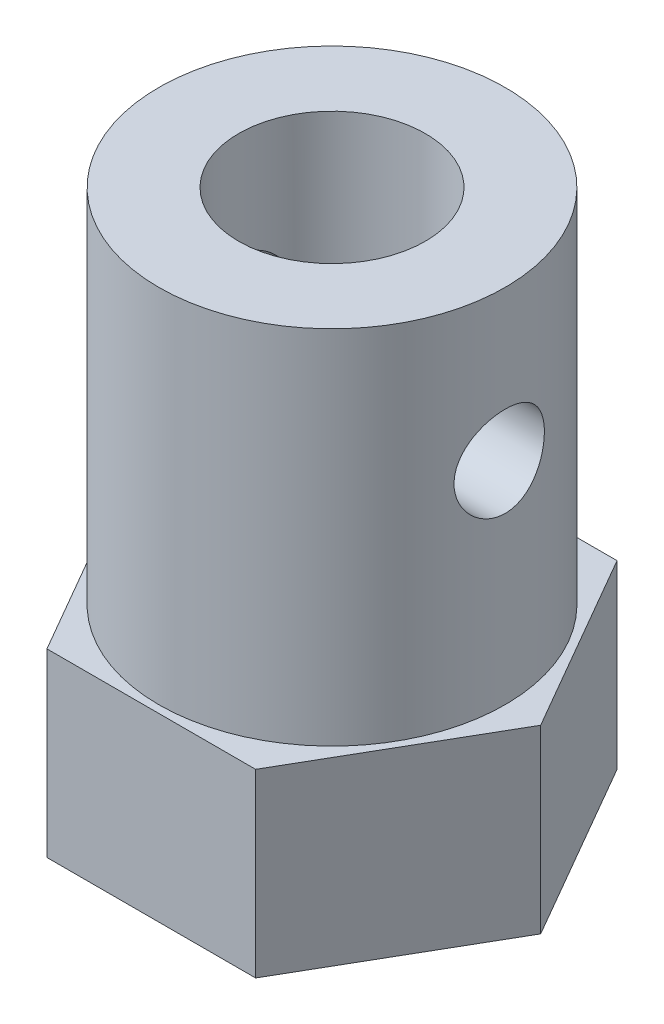
SolidWorks part; units mm, degrees
ref_plane "Front Plane" through (0, 0, 0) normal (0, 0, 1) x (1, 0, 0)
ref_plane "Top Plane" through (0, 0, 0) normal (0, 1, 0) x (1, 0, 0)
ref_plane "Right Plane" through (0, 0, 0) normal (1, 0, 0) x (0, 0, -1)
sketch "Sketch1" plane through (0, 0, 0) normal (0, 1, 0) x (1, 0, 0)
  line L1 (6.9282, 0) -> (3.4641, 6)
  line L2 (3.4641, 6) -> (-3.4641, 6)
  line L3 (-3.4641, 6) -> (-6.9282, 0)
  line L4 (-6.9282, 0) -> (-3.4641, -6)
  line L5 (-3.4641, -6) -> (3.4641, -6)
  line L6 (3.4641, -6) -> (6.9282, 0)
  circle A0 centre (0, 0) radius 6 construction
  circle A1 centre (0, 0) radius 1.5
  dimension "D2" = 3
  dimension "D1" = 12
extrude "Boss-Extrude1" add sketch "Sketch1" along normal blind 6
sketch "Sketch2" plane through (0, 6, 0) normal (0, 1, 0) x (1, 0, 0)
  circle A0 centre (0, 0) radius 5.75
  circle A1 centre (0, 0) radius 3.1
  dimension "D1" = 11.5
  dimension "D2" = 3.1
extrude "Boss-Extrude2" add sketch "Sketch2" along normal blind 12
sketch "Sketch3" plane through (0, 0, 0) normal (1, 0, 0) x (0, 0, -1)
  line L0 (5.75, 18) -> (-5.75, 18) construction
  circle A0 centre (0, 13) radius 1.5
  dimension "D1" = 3
  dimension "D2" = 5
extrude "Cut-Extrude1" cut sketch "Sketch3" against normal mid plane 12 contours A0
